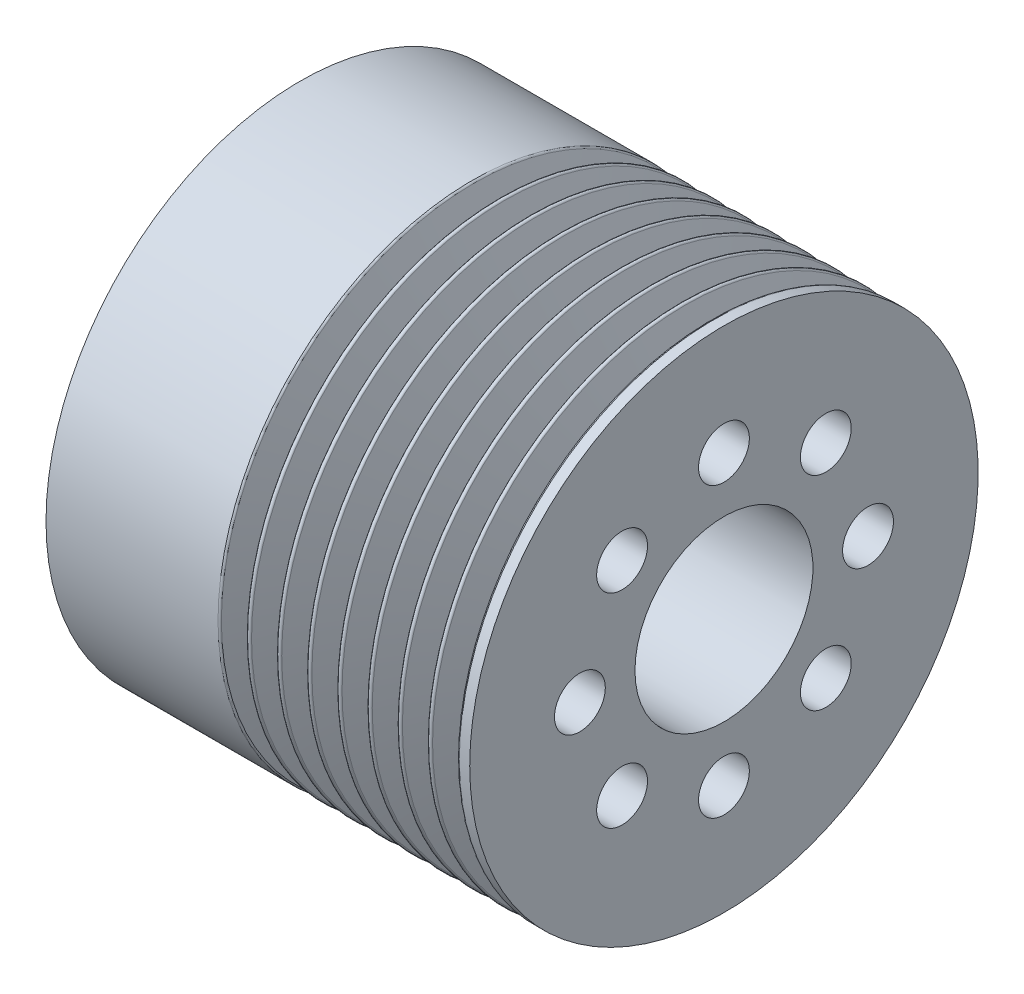
SolidWorks part; units mm, degrees
material "2018 Alloy"
ref_plane "Front Plane" through (0, 0, 0) normal (0, 0, 1) x (1, 0, 0)
ref_plane "Top Plane" through (0, 0, 0) normal (0, 1, 0) x (1, 0, 0)
ref_plane "Right Plane" through (0, 0, 0) normal (1, 0, 0) x (0, 0, -1)
sketch "Sketch1" plane through (0, 0, 0) normal (0, 0, 1) x (1, 0, 0)
  line L0 (49, 10.5) -> (49, 0) construction
  line L1 (49, 10.5) -> (49, 30)
  line L2 (49, 30) -> (-1, 30)
  line L3 (-1, 30) -> (-1, 21.5)
  line L4 (49, 10.5) -> (31.5, 10.5)
  line L5 (0, 0) -> (49, 0) construction
  line L6 (-1, 21.5) -> (31.5, 21.5)
  line L8 (0, 8.3175) -> (0, 0) construction
  line L9 (31.5, 10.5) -> (31.5, 21.5)
  dimension "D1" = 50
  dimension "D2" = 60
  dimension "D3" = 31.5
  dimension "D4" = 43
  dimension "D5" = 49
  dimension "D8" = 21
revolve "Revolve1" add sketch "Sketch1" angle 360 about L5
sketch "Sketch2" plane through (0, 0, 0) normal (0, 0, 1) x (1, 0, 0)
  line L0 (47.5458, 29.8376) -> (46.281, 26.4546)
  line L1 (45.719, 26.4546) -> (44.4542, 29.8376)
  line L2 (47.5458, 29.8376) -> (47.6066, 30) construction
  line L3 (49, 30) -> (-1, 30) construction
  line L4 (44.4542, 29.8376) -> (44.3934, 30) construction
  line L5 (49, -30) -> (49, 30) construction
  line L6 (47.78, 30) -> (44.22, 30)
  line L7 (0, 0) -> (49, 0) construction
  arc A0 (47.5458, 29.8376) -> (47.78, 30) centre (47.78, 29.75) cw
  arc A1 (44.4542, 29.8376) -> (44.22, 30) centre (44.22, 29.75) ccw
  arc A2 (46.281, 26.4546) -> (45.719, 26.4546) centre (46, 26.5597) cw
  dimension "D2" = 0.25
  dimension "D3" = 0.3
  dimension "D1" = 41
  dimension "D4" = 3.56
  dimension "D5" = 3
revolve "Cut-Revolve1" cut sketch "Sketch2" angle 360 about L7
pattern_linear "LPattern1" count 8 spacing 3.56 along (-1, 0, 0) of "Cut-Revolve1"
sketch "Sketch3" plane through (49, 0, 0) normal (1, 0, 0) x (0, 0, -1)
  circle A0 centre (0, 0) radius 17 construction
  circle A1 centre (0, 17) radius 3
  circle A2 centre (12.0208, 12.0208) radius 3
  circle A3 centre (17, 0) radius 3
  circle A4 centre (12.0208, -12.0208) radius 3
  circle A5 centre (0, -17) radius 3
  circle A6 centre (-12.0208, -12.0208) radius 3
  circle A7 centre (-17, 0) radius 3
  circle A8 centre (-12.0208, 12.0208) radius 3
  dimension "D1" = 34
  dimension "D2" = 6
  dimension "D3" = 8
extrude "Cut-Extrude1" cut sketch "Sketch3" against normal up to surface (17.5 mm away) up to face at (31.5, 0, 10.5)
